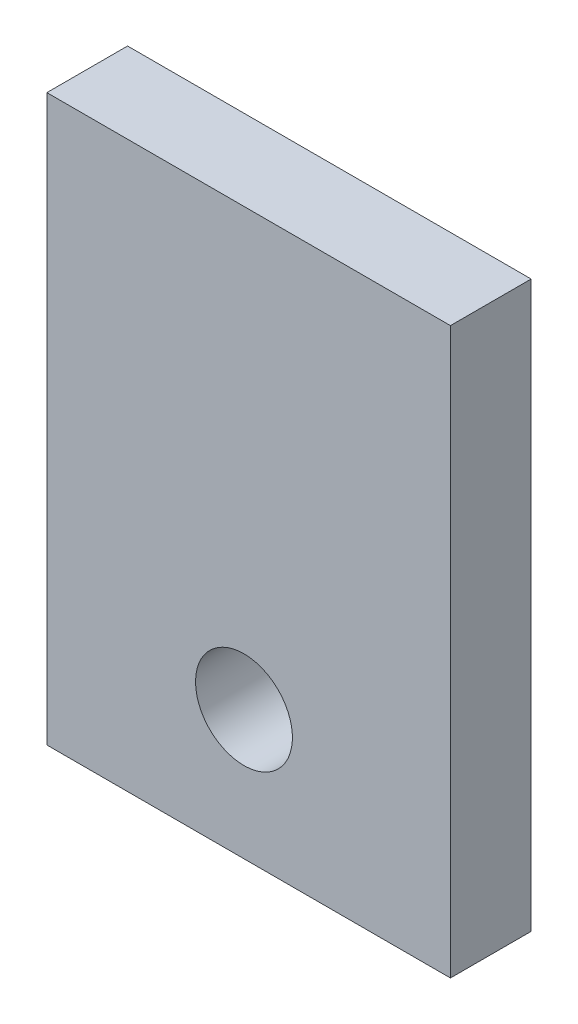
SolidWorks part; units mm, degrees
ref_plane "Ebene vorne" through (0, 0, 0) normal (0, 0, 1) x (1, 0, 0)
ref_plane "Ebene oben" through (0, 0, 0) normal (0, 1, 0) x (1, 0, 0)
ref_plane "Ebene rechts" through (0, 0, 0) normal (1, 0, 0) x (0, 0, -1)
sketch "Skizze1" plane through (0, 0, 0) normal (0, 0, 1) x (1, 0, 0)
  line L1 (0, 0) -> (12, 0)
  line L2 (0, 0) -> (0, -10)
  line L3 (0, -10) -> (12, -10)
  line L4 (12, 0) -> (12, -10)
  dimension "D1" = 12
  dimension "D2" = 10
extrude "Halterungssockel" add sketch "Skizze1" along normal blind 2
sketch "Skizze2" plane through (0, 0, 2) normal (0, 0, 1) x (1, 0, 0)
  line L9 (-7.1018, 10) -> (17.8982, 10)
  line L10 (-7.1018, 10) -> (-7.1018, -25)
  line L11 (-7.1018, -25) -> (17.8982, -25)
  line L12 (17.8982, 10) -> (17.8982, -25)
  dimension "D1" = 25
  dimension "D2" = 35
  dimension "D3" = 10
extrude "Aufsatz-Linear austragen2" add sketch "Skizze2" along normal blind 5
sketch "Skizze3" plane through (0, 0, 0) normal (0, 0, -1) x (-1, 0, 0)
  circle A0 centre (-5.1084, -17) radius 3
  dimension "D2" = 6
  dimension "D1" = 17
extrude "Schnitt-Linear austragen1" cut sketch "Skizze3" against normal through all and the other way through all contours A0
